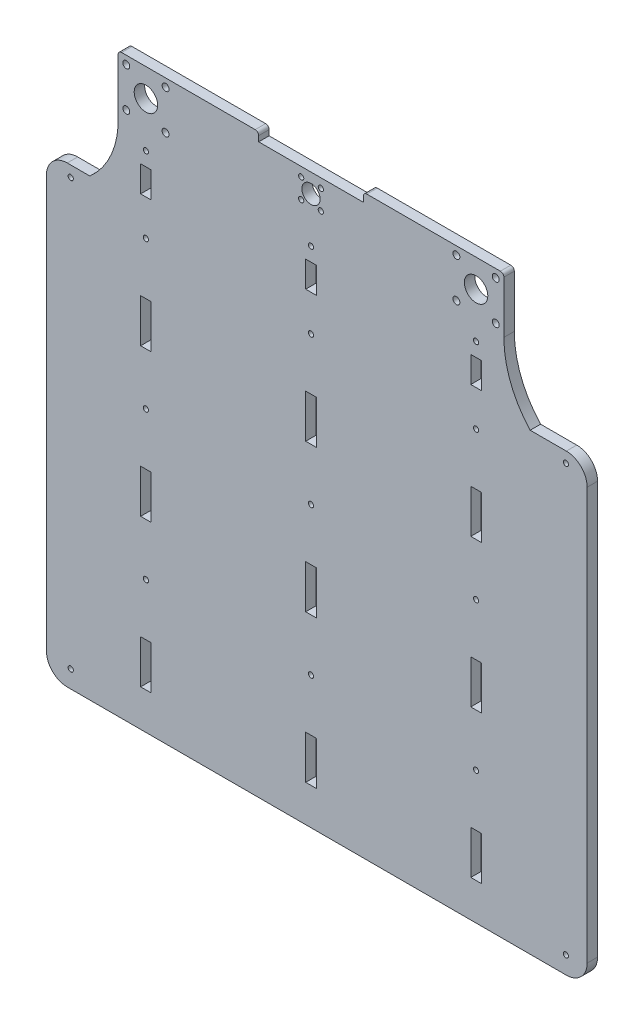
SolidWorks part; units mm, degrees
ref_plane "Alzado" through (0, 0, 0) normal (0, 0, 1) x (1, 0, 0)
ref_plane "Planta" through (0, 0, 0) normal (0, 1, 0) x (1, 0, 0)
ref_plane "Vista lateral" through (0, 0, 0) normal (1, 0, 0) x (0, 0, -1)
sketch "Croquis1" plane through (0, 0, 0) normal (0, 0, 1) x (1, 0, 0)
  line L0 (32.1154, 16) -> (87.6356, 16)
  line L1 (-109, 16) -> (-87.6356, 16)
  line L2 (-111, 14) -> (-111, -16)
  line L3 (-135.2776, -315.9124) -> (-119.3643, -315.9124)
  line L4 (-87.6356, 16) -> (-44.6644, 16)
  line L5 (30.1154, 14) -> (30.1154, 10.91)
  line L6 (0, 0) -> (0, 78.8056) construction
  line L7 (30.1154, 10.91) -> (-30.1154, 10.91)
  line L8 (-111, 0) -> (-111, -16)
  line L9 (-111, -16) -> (-111, 16)
  line L10 (-44.6644, 16) -> (-32.1154, 16)
  line L11 (-119.3643, -315.9124) -> (119.3644, -315.9124)
  line L12 (111, 14) -> (111, -16)
  line L13 (109, 16) -> (87.6356, 16)
  line L14 (-30.1154, 14) -> (-30.1154, 10.91)
  line L15 (-8.3, -8.3) -> (8.3, 8.3) construction
  line L16 (-127.2776, -54.7017) -> (126.134, -54.7017) construction
  line L17 (-95, 0) -> (-95, -315.9124) construction
  line L18 (119.3644, -315.9124) -> (130.2951, -315.9124)
  line L19 (-8.3, 8.3) -> (8.3, -8.3) construction
  line L20 (-127.2776, -54.7017) -> (-135.2776, -54.7017)
  line L21 (-111, 16) -> (-79, -16) construction
  line L22 (-111, -16) -> (-79, 16) construction
  line L23 (-135.2776, -54.7017) -> (-140.2776, -54.7017)
  line L24 (-138.2776, -60.9124) -> (-136.7776, -60.9124) construction
  line L25 (-111, -16) -> (-79, -16) construction
  line L26 (-135.2776, -315.9124) -> (-140.2776, -315.9124)
  line L27 (-152.2776, -66.7017) -> (-152.2776, -303.9124)
  line L28 (-79, -16) -> (111, -16) construction
  line L29 (130.2951, -315.9124) -> (146.9429, -315.9124)
  line L30 (158.9429, -70.771) -> (158.9429, -303.9124)
  line L31 (145.2224, -60.9124) -> (146.7224, -60.9124) construction
  line L32 (126.134, -54.7017) -> (146.9429, -54.7017)
  line L33 (0, 0) -> (0.0001, -316) construction
  line L34 (95, 0) -> (95, -316) construction
  line L35 (158.9429, -66.7017) -> (158.9429, -70.771)
  line L36 (-98.05, -184.7017) -> (-91.95, -184.7017)
  line L37 (-98.05, -34) -> (-91.95, -34)
  line L38 (-98.05, -34) -> (-98.05, -49)
  line L39 (-98.05, -49) -> (-91.95, -49)
  line L40 (-91.95, -34) -> (-91.95, -49)
  line L41 (-98.05, -99.7017) -> (-91.95, -99.7017)
  line L42 (-98.05, -99.7017) -> (-98.05, -124.7017)
  line L43 (-98.05, -124.7017) -> (-91.95, -124.7017)
  line L44 (-91.95, -99.7017) -> (-91.95, -124.7017)
  line L45 (-98.05, -184.7017) -> (-98.05, -209.7017)
  line L46 (-98.05, -209.7017) -> (-91.95, -209.7017)
  line L47 (-91.95, -184.7017) -> (-91.95, -209.7017)
  line L48 (-98.05, -269.7017) -> (-91.95, -269.7017)
  line L49 (-98.05, -269.7017) -> (-98.05, -294.7017)
  line L50 (-98.05, -294.7017) -> (-91.95, -294.7017)
  line L51 (-91.95, -269.7017) -> (-91.95, -294.7017)
  line L52 (-98.05, -99.7017) -> (-98.05, -184.7017) construction
  line L53 (98.05, -99.7017) -> (98.0501, -184.7017) construction
  line L54 (95, 0) -> (95.0001, -315.9124) construction
  line L55 (127.2776, -54.7016) -> (-126.134, -54.7018) construction
  line L56 (91.9501, -269.7017) -> (91.9501, -294.7017)
  line L57 (98.0501, -294.7017) -> (91.9501, -294.7017)
  line L58 (98.0501, -269.7017) -> (98.0501, -294.7017)
  line L59 (98.0501, -269.7017) -> (91.9501, -269.7017)
  line L60 (91.9501, -184.7017) -> (91.9501, -209.7017)
  line L61 (98.0501, -209.7017) -> (91.9501, -209.7017)
  line L62 (98.0501, -184.7017) -> (98.0501, -209.7017)
  line L63 (91.95, -99.7017) -> (91.9501, -124.7017)
  line L64 (98.0501, -124.7017) -> (91.9501, -124.7017)
  line L65 (98.05, -99.7017) -> (98.0501, -124.7017)
  line L66 (98.05, -99.7017) -> (91.95, -99.7017)
  line L67 (91.95, -34) -> (91.95, -49)
  line L68 (98.05, -49) -> (91.95, -49)
  line L69 (98.05, -34) -> (98.05, -49)
  line L70 (98.05, -34) -> (91.95, -34)
  line L71 (98.0501, -184.7017) -> (91.9501, -184.7017)
  line L72 (3.05, -99.7892) -> (3.0501, -184.7892) construction
  line L73 (-3.0499, -269.7892) -> (-3.0499, -294.7892)
  line L74 (3.0501, -294.7892) -> (-3.0499, -294.7892)
  line L75 (3.0501, -269.7892) -> (3.0501, -294.7892)
  line L76 (3.0501, -269.7892) -> (-3.0499, -269.7892)
  line L77 (-3.0499, -184.7892) -> (-3.0499, -209.7892)
  line L78 (3.0501, -209.7892) -> (-3.0499, -209.7892)
  line L79 (3.0501, -184.7892) -> (3.0501, -209.7892)
  line L80 (-3.05, -99.7892) -> (-3.05, -124.7892)
  line L81 (3.05, -124.7892) -> (-3.05, -124.7892)
  line L82 (3.05, -99.7892) -> (3.05, -124.7892)
  line L83 (3.05, -99.7892) -> (-3.05, -99.7892)
  line L84 (-3.05, -34) -> (-3.05, -49)
  line L85 (3.05, -49) -> (-3.05, -49)
  line L86 (3.05, -34) -> (3.05, -49)
  line L87 (3.05, -34) -> (-3.05, -34)
  line L88 (3.0501, -184.7892) -> (-3.0499, -184.7892)
  line L89 (95, -26) -> (-95, -26) construction
  circle A0 centre (0, 0) radius 5.25
  circle A1 centre (-95, 0) radius 6.75
  circle A2 centre (95, 0) radius 6.75
  circle A3 centre (146.7224, -60.9124) radius 1.5
  circle A4 centre (-83.6863, 11.3137) radius 2
  circle A5 centre (-106.3137, 11.3137) radius 2
  circle A6 centre (-83.6863, -11.3137) radius 2
  circle A7 centre (-106.3137, -11.3137) radius 2
  circle A8 centre (106.3137, -11.3137) radius 2
  circle A9 centre (83.6863, -11.3137) radius 2
  circle A10 centre (83.6863, 11.3137) radius 2
  arc A11 (-111, -16) -> (-127.2776, -54.7017) centre (-158.9474, -18.6077) cw
  arc A12 (111, -16) -> (126.134, -54.7017) centre (168.0523, -16) ccw
  arc A13 (-140.2776, -315.9124) -> (-152.2776, -303.9124) centre (-140.2776, -303.9124) cw
  arc A14 (158.9429, -303.9124) -> (146.9429, -315.9124) centre (146.9429, -303.9124) cw
  arc A15 (158.9429, -66.7017) -> (146.9429, -54.7017) centre (146.9429, -66.7017) ccw
  circle A16 centre (5.6569, 5.6569) radius 1.5
  circle A17 centre (-5.6569, 5.6569) radius 1.5
  circle A18 centre (-5.6569, -5.6569) radius 1.5
  circle A19 centre (5.6569, -5.6569) radius 1.5
  arc A20 (-140.2776, -54.7017) -> (-152.2776, -66.7017) centre (-140.2776, -66.7017) ccw
  circle A21 centre (146.7224, -305.9124) radius 1.5
  circle A22 centre (-138.2776, -305.9124) radius 1.5
  circle A23 centre (-138.2776, -60.9124) radius 1.5
  circle A24 centre (-95, -26) radius 1.5
  circle A25 centre (-95, -69.7017) radius 1.5
  circle A26 centre (-95, -154.7017) radius 1.5
  circle A27 centre (-95, -239.7017) radius 1.5
  circle A28 centre (95.0001, -239.7017) radius 1.5
  arc A29 (109, 16) -> (111, 14) centre (109, 14) cw
  arc A30 (-111, 14) -> (-109, 16) centre (-109, 14) cw
  circle A31 centre (95.0001, -154.7017) radius 1.5
  circle A32 centre (95, -69.7017) radius 1.5
  circle A33 centre (95, -26) radius 1.5
  circle A34 centre (0.0001, -239.7892) radius 1.5
  arc A35 (-32.1154, 16) -> (-30.1154, 14) centre (-32.1154, 14) cw
  circle A36 centre (0.0001, -154.7892) radius 1.5
  circle A37 centre (106.3137, 11.3137) radius 2
  arc A38 (30.1154, 14) -> (32.1154, 16) centre (32.1154, 14) cw
  circle A39 centre (0, -69.7892) radius 1.5
  circle A40 centre (0.0046, -26) radius 1.5
  point P71 (0, 16)
  point P98 (111, 16)
  point P101 (-111, 16)
  point P106 (30.1154, 16)
  point P108 (-147.2776, -54.7017)
  dimension "D3" = 285
  dimension "D4" = 12
  dimension "D5" = 10.5
  dimension "D6" = 14
  dimension "D7" = 285
  dimension "D8" = 13.5
  dimension "D9" = 245
  dimension "D10" = 4
  dimension "D11" = 222
  dimension "D12" = 16
  dimension "D13" = 10
  dimension "D16" = 190
  dimension "D2" = 13.5
  dimension "D18" = 14
  dimension "D21" = 4
  dimension "D19" = 4
  dimension "D20" = 4
  dimension "D22" = 2
  dimension "D24" = 12
  dimension "D25" = 12
  dimension "D34" = 15
  dimension "D14" = 16
  dimension "D15" = 6.1
  dimension "D17" = 95
  dimension "D23" = 20
  dimension "D26" = 5.2532
  dimension "D27" = 5.2532
  dimension "D28" = 11.3137
  dimension "D29" = 11.3137
  dimension "D30" = 11.3137
  dimension "D31" = 11.3137
  dimension "D32" = 15
  dimension "D33" = 8
  dimension "D35" = 25
  dimension "D36" = 30
  dimension "D38" = 85
  dimension "D39" = 10
  dimension "D40" = 10
  dimension "D41" = 20.7017
  dimension "D37" = 3
extrude "Saliente-Extruir1" add sketch "Croquis1" along normal blind 6
